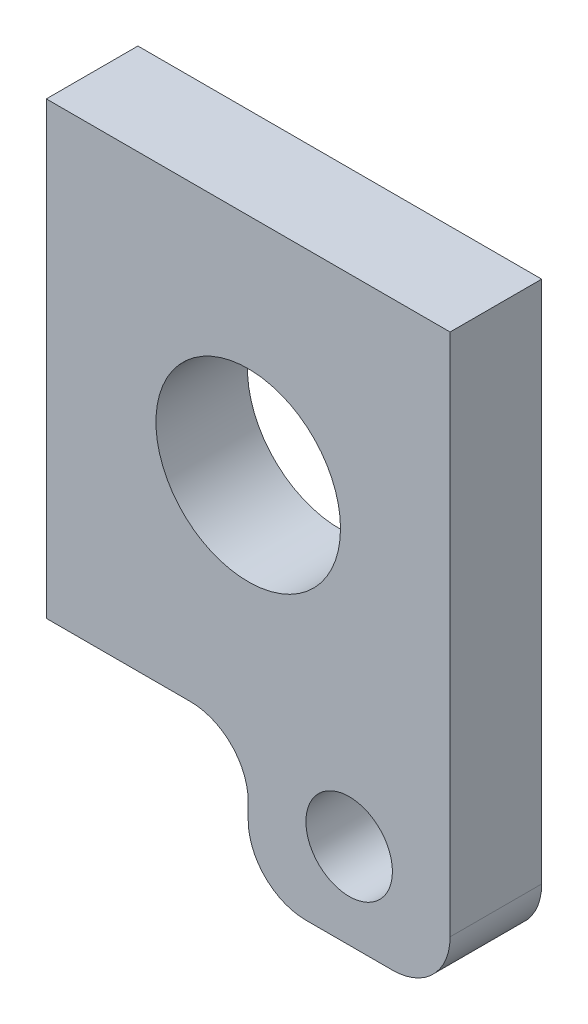
SolidWorks part; units mm, degrees
material "Delrin 2700 NC010, Low Viscosity Acetal Copolymer (SS)"
ref_plane "Front" through (0, 0, 0) normal (0, 0, 1) x (1, 0, 0)
ref_plane "Top" through (0, 0, 0) normal (0, 1, 0) x (1, 0, 0)
ref_plane "Right" through (0, 0, 0) normal (1, 0, 0) x (0, 0, -1)
sketch "Sketch1" plane through (0, 0, 0) normal (0, 0, 1) x (1, 0, 0)
  line L1 (-3.5, -3.9) -> (3.5, -3.9) construction
  line L2 (-3.5, -3.9) -> (-3.5, 3.9)
  line L3 (-3.5, 3.9) -> (3.5, 3.9)
  line L4 (3.5, -3.9) -> (3.5, 3.9)
  line L5 (-3.5, -3.9) -> (3.5, 3.9) construction
  line L6 (-3.5, 3.9) -> (3.5, -3.9) construction
  line L7 (0, -6.2812) -> (3.5, -6.2812)
  line L8 (3.5, -6.2812) -> (3.5, -3.9)
  line L9 (0, -6.2812) -> (0, -3.9)
  line L10 (0, -3.9) -> (-3.5, -3.9)
  line L11 (1.75, -4.7) -> (1.75, -6.2812) construction
  circle A0 centre (0, 0) radius 1.6
  circle A1 centre (1.75, -4.7) radius 0.75
  point P0 (0, 0)
  dimension "D2" = 7
  dimension "D4" = 1.5
  dimension "D5" = 0.8
  dimension "D6" = 3.2
  dimension "D1" = 7.8
  dimension "D3" = 2.3813
extrude "Boss-Extrude1" add sketch "Sketch1" along normal blind 1.5875
other "Move Face2" face at (1.75, -6.2812, 0.7937) parameters "D1"=0.1
fillet "Fillet3" radius 1 3 edges at (3.5, -6.1812, 0.7937) (0, -6.1812, 0.7937) (0, -3.9, 0.7937)
other "Move Face3" [suppressed] parameters "D1"=0.0762
